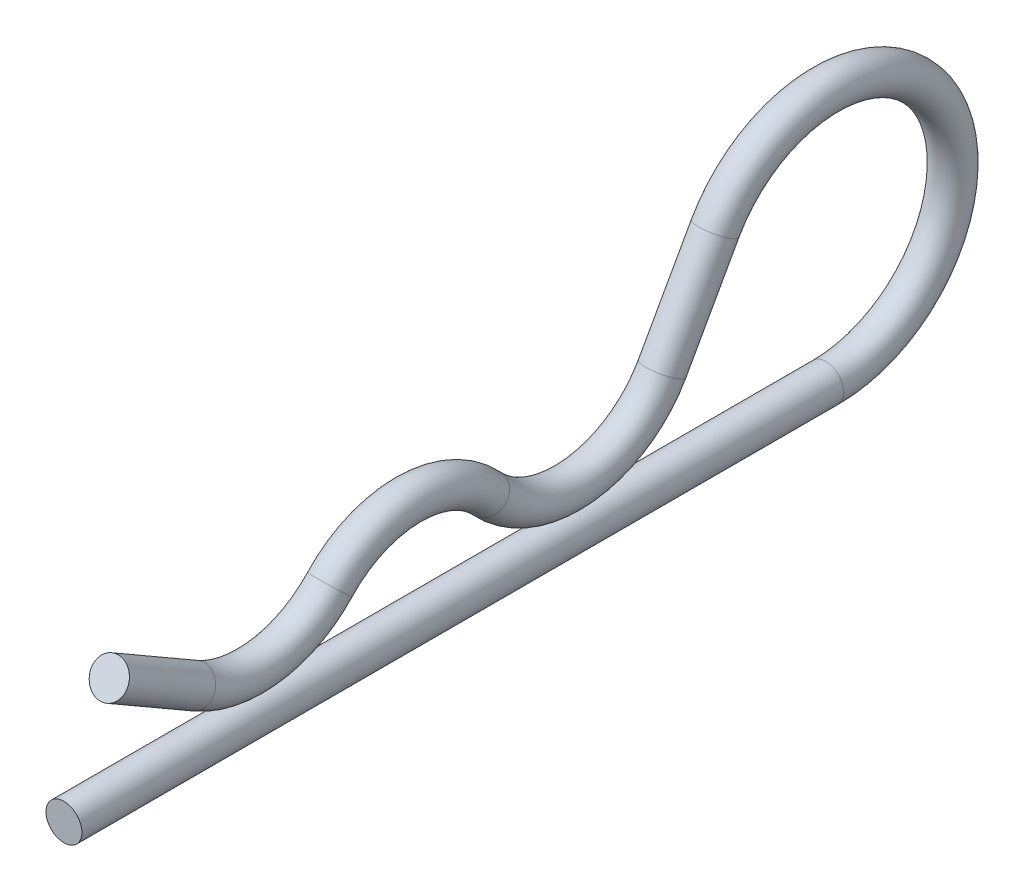
SolidWorks part; units mm, degrees
ref_plane "Front" through (0, 0, 0) normal (0, 0, 1) x (1, 0, 0)
ref_plane "Top" through (0, 0, 0) normal (0, 1, 0) x (1, 0, 0)
ref_plane "Right" through (0, 0, 0) normal (1, 0, 0) x (0, 0, -1)
sketch "Sketch1" plane through (0, 0, 0) normal (1, 0, 0) x (0, 0, -1)
  line L0 (-16.6751, 0) -> (16.6751, 0) construction
  line L1 (-8.5369, 0.7874) -> (-8.5369, 2.5197) construction
  line L2 (23.0124, 0) -> (23.0124, 5.5499) construction
  line L3 (23.0124, 5.5499) -> (22.225, 5.5499) construction
  line L4 (-16.6751, 0) -> (-16.6751, 0.7874) construction
  line L5 (23.0124, 0) -> (-16.6751, 0) construction
  line L6 (-10.9181, 2.2916) -> (-14.6907, 4.4697) construction
  line L7 (-1.5939, 4.6911) -> (-1.5939, 0) construction
  line L8 (-16.6751, 0) -> (-16.6751, -0.7874) construction
  line L13 (11.8287, 8.2542) -> (9.508, 4.0954) construction
  circle A0 centre (16.6751, 5.5499) radius 4.7625 construction
  arc A1 (1.8514, 3.1838) -> (-5.0391, 3.1838) centre (-1.5939, 0) ccw construction
  arc A6 (-5.0391, 3.1838) -> (-10.9181, 2.2916) centre (-8.5369, 6.416) cw construction
  arc A8 (9.508, 4.0954) -> (1.8514, 3.1838) centre (5.3492, 6.416) cw construction
  arc A9 (16.6751, 0) -> (11.8287, 8.2542) centre (16.6751, 5.5499) ccw construction
  point P2 (0, 0)
  point P5 (-8.5369, 1.6535)
  point P16 (-8.5369, 1.6535)
  dimension "D1" = 4.7625
  dimension "Eye Diameter" = 9.525
  dimension "D5" = 1.9844
  dimension "D9" = 30
  dimension "D11" = 0.7874
  dimension "D3" = 0.7874
  dimension "Length" = 39.6875
  dimension "Wire Diameter" = 1.5748
  dimension "D4" = 4.7625
  dimension "D6" = 1.7323
  dimension "D2" = 15.0812
ref_plane "Plane1" through (0, 0, 16.6751) normal (0, 0, 1) x (1, 0, 0)
sketch "Sketch2" plane through (0, 0, 16.6751) normal (0, 0, 1) x (1, 0, 0)
  circle A0 centre (0, 0) radius 0.7874
sketch "Sketch3" plane through (0, 0, 0) normal (1, 0, 0) x (0, 0, -1)
  line L0 (-10.9181, 2.2916) -> (-14.6907, 4.4697) construction
  line L1 (11.8287, 8.2542) -> (9.508, 4.0954) construction
  line L2 (-16.6751, 0) -> (16.6751, 0) construction
  line L3 (-10.9181, 2.2916) -> (-14.6907, 4.4697)
  line L4 (11.8287, 8.2542) -> (9.508, 4.0954)
  line L5 (-16.6751, 0) -> (16.6751, 0)
  arc A0 (-10.9181, 2.2916) -> (-5.0391, 3.1838) centre (-8.5369, 6.416) ccw construction
  arc A1 (1.8514, 3.1838) -> (-5.0391, 3.1838) centre (-1.5939, 0) ccw construction
  arc A2 (1.8514, 3.1838) -> (9.508, 4.0954) centre (5.3492, 6.416) ccw construction
  arc A3 (16.6751, 0) -> (11.8287, 8.2542) centre (16.6751, 5.5499) ccw construction
  arc A4 (-10.9181, 2.2916) -> (-5.0391, 3.1838) centre (-8.5369, 6.416) ccw
  arc A5 (1.8514, 3.1838) -> (-5.0391, 3.1838) centre (-1.5939, 0) ccw
  arc A6 (1.8514, 3.1838) -> (9.508, 4.0954) centre (5.3492, 6.416) ccw
  arc A7 (16.6751, 0) -> (11.8287, 8.2542) centre (16.6751, 5.5499) ccw
sweep "Sweep1" add profiles "Sketch2" path "Sketch3"
equation "\"D11@Sketch1\" = \"Wire Diameter@Sketch1\" / 2"
equation "\"D1@Sketch1\"=\"Eye Diameter@Sketch1\" / 2"
equation "\"D3@Sketch1\" = \"D11@Sketch1\""
equation "\"D5@Sketch1\" = \"Length@Sketch1\" * .05"
equation "\"D4@Sketch1\"=\"Eye Diameter@Sketch1\"/2"
equation "\"D6@Sketch1\"=\"Wire Diameter@Sketch1\"*1.1"
equation "\"D2@Sketch1\"=( \"Length@Sketch1\" - \"Eye Diameter@Sketch1\" )  / 2"
